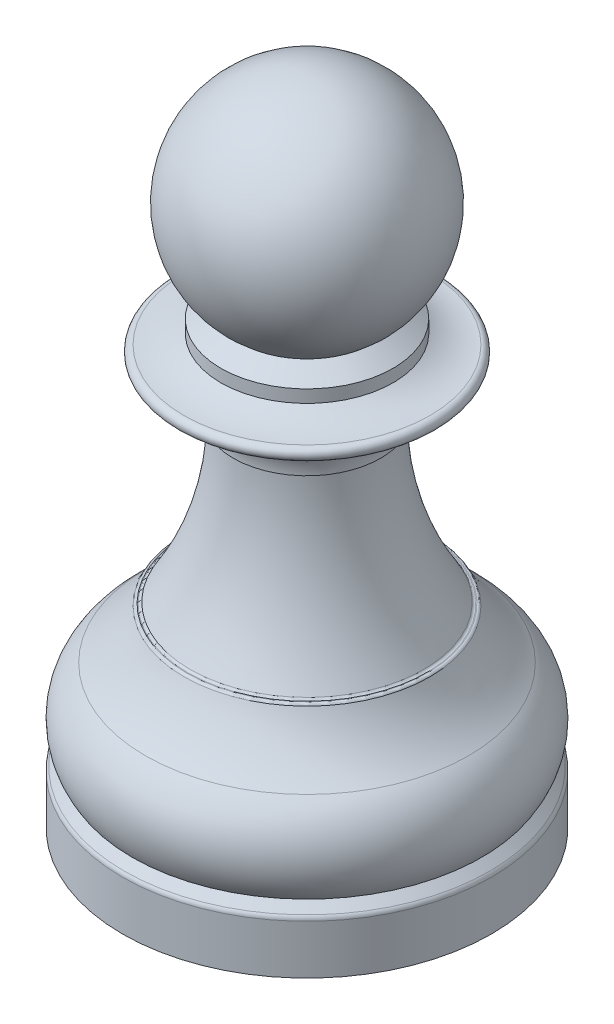
SolidWorks part; units mm, degrees
other "Piece" parameters "D1"=8
ref_plane "Front Plane" through (0, 0, 0) normal (0, 0, 1) x (1, 0, 0)
ref_plane "Top Plane" through (0, 0, 0) normal (0, 1, 0) x (1, 0, 0)
ref_plane "Right Plane" through (0, 0, 0) normal (1, 0, 0) x (0, 0, -1)
sketch "Sketch1" plane through (0, 0, 0) normal (0, 0, 1) x (1, 0, 0)
  line L0 (-15.0008, 0) -> (-15.0008, 4)
  line L1 (-14.2079, 5) -> (-14.8544, 4.3536)
  line L2 (-7, 34.8038) -> (-7, 35.8258)
  line L3 (-5.5, 36.8761) -> (-7, 35.8258)
  line L4 (-10, 33.5) -> (-10, 29) construction
  line L5 (-15.0008, 0) -> (0, 0)
  line L6 (0, 53) -> (0, 0)
  line L7 (0, 0) -> (0, -3.0952) construction
  line L8 (-6, 29) -> (-5.75, 29)
  line L9 (-5.75, 29) -> (-6, 29)
  line L10 (-6, 29) -> (-6, 32.7132) construction
  line L11 (-5.75, 29) -> (-5.75, 35.7914) construction
  line L12 (-9.7727, 15.7558) -> (-9.7123, 15.7558)
  arc A0 (-14.8544, 4.3536) -> (-15.0008, 4) centre (-14.5008, 4) ccw
  arc A1 (-13.1255, 11.6052) -> (-14.2079, 5) centre (-10.0008, 7.7019) ccw
  arc A2 (-13.1255, 11.6052) -> (-10, 15.61) centre (-20, 20.1925) ccw
  arc A3 (-9.7727, 15.7558) -> (-10, 15.61) centre (-9.7727, 15.5058) ccw
  arc A4 (-9.7123, 15.7558) -> (-9.5, 15.8737) centre (-9.7123, 16.0058) ccw
  arc A5 (-9.5, 15.8737) -> (-6.422, 23.2605) centre (-30.5981, 29) ccw
  arc A6 (-6.422, 23.2605) -> (-5.75, 29) centre (-30.5981, 29) ccw
  arc A7 (-6, 29) -> (-6.7812, 31.3748) centre (-10, 29) ccw
  arc A8 (-6.7812, 31.3748) -> (-10, 33) centre (-10, 29) ccw
  arc A9 (-10, 34) -> (-10, 33) centre (-10, 33.5) ccw
  arc A10 (-10, 34) -> (-7, 34.8038) centre (-10, 40) ccw
  arc A11 (0, 53) -> (-5.5, 36.8761) centre (0, 44) ccw
  dimension "D3" = 0.5
  dimension "D8" = 5
  dimension "D12" = 11
  dimension "D15" = 0.25
  dimension "D23" = 10
  dimension "D26" = 0.5
  dimension "D27" = 6
  dimension "D28" = 9
  dimension "D33" = 10
  dimension "D1" = 53
  dimension "D2" = 30.0016
  dimension "D4" = 14.5008
  dimension "D5" = 135
  dimension "D6" = 5
  dimension "D7" = 4
  dimension "D10" = 20
  dimension "D11" = 10.5
  dimension "D13" = 10
  dimension "D14" = 0.25
  dimension "D16" = 5.75
  dimension "D19" = 9.5
  dimension "D24" = 6
  dimension "D29" = 7
  dimension "D30" = 5.5
  dimension "D31" = 55
revolve "Revolve1" add sketch "Sketch1" angle 360 about L7
scale "Scale2" scale about origin uniform scaling yes scale factor 0.766667
sketch "Sketch5" plane through (0, 0, 0) normal (0, -1, 0) x (1, 0, 0)
  point P0 (0, 0)
sketch "Sketch2" plane through (0, 0, 0) normal (0, -1, 0) x (1, 0, 0)
  circle A0 centre (0, 0) radius 10.2
  dimension "D1" = 20.4
extrude "Cut-Extrude1" cut sketch "Sketch2" against normal blind 8
sketch "Sketch6" plane through (0, 8, 0) normal (0, -1, 0) x (1, 0, 0)
  circle A0 centre (0, 0) radius 4.4
  dimension "D1" = 8.8
extrude "Cut-Extrude2" [suppressed] cut sketch "Sketch6" against normal blind 5
sketch "Sketch7" [suppressed] plane through (0, 10, 0) normal (0, -1, 0) x (1, 0, 0)
  circle A0 centre (0, 0) radius 2.2
  dimension "D1" = 4.4
extrude "Cut-Extrude3" [suppressed] cut sketch "Sketch7" against normal blind 13
sketch "Sketch9" plane through (0, 0, 0) normal (0, 0, 1) x (1, 0, 0)
  line L0 (-10.75, 1) -> (0, 1)
  line L1 (-10.75, 1) -> (-10.75, 0)
  line L2 (-10.75, 0) -> (0, 0)
  line L3 (0, 0) -> (0, -1) construction
  line L4 (0, 0) -> (0, 1)
  point P0 (0, 0.75)
  point P4 (-10.2, 0)
  dimension "D1" = 10.2
  dimension "D2" = 1
  dimension "D3" = 0.55
  dimension "D4" = 21.5
revolve "Cut-Revolve1" [suppressed] cut sketch "Sketch9" angle 360 about L3
sketch "Sketch10" plane through (0, 0, 0) normal (0, 0, 1) x (1, 0, 0)
  line L0 (0, 0) -> (-10.55, 0)
  line L1 (0, 0) -> (0, 1)
  line L2 (0, 1) -> (-10.55, 1)
  line L3 (-10.55, 0) -> (-10.55, 1)
  line L4 (0, 0) -> (0, -1.6825) construction
  line L5 (-10.2, 1) -> (-10.2, 0.5)
  line L6 (-10.2, 0.5) -> (0, 0.5)
  dimension "D1" = 21.1
  dimension "D2" = 1
  dimension "D3" = 0.5
  dimension "D4" = 20.4
revolve "Base (White Pawn)" [suppressed] add sketch "Sketch10" angle 360 about L4
sketch "Sketch11" [suppressed] plane through (0, 0, 0) normal (0, 0, 1) x (1, 0, 0)
  line L0 (10.2, 0.5) -> (-10.2, 0.5) construction
  line L1 (-7.5, 2.5) -> (7.5, 2.5)
  line L2 (-7.5, 2.5) -> (-7.5, 0.5)
  line L3 (-7.5, 0.5) -> (7.5, 0.5)
  line L4 (7.5, 2.5) -> (7.5, 0.5)
  line L5 (-7.5, 2.5) -> (7.5, 0.5) construction
  line L6 (-7.5, 0.5) -> (7.5, 2.5) construction
  line L8 (-7.5, 4.5) -> (7.5, 4.5)
  line L9 (-7.5, 4.5) -> (-7.5, 2.5)
  line L10 (-7.5, 2.5) -> (7.5, 2.5)
  line L11 (7.5, 4.5) -> (7.5, 2.5)
  line L12 (-7.5, 4.5) -> (7.5, 2.5) construction
  line L13 (-7.5, 2.5) -> (7.5, 4.5) construction
  line L15 (0, 4.5) -> (0, 0.5) construction
  line L16 (-10.2, 7) -> (10.2, 7) construction
  point P0 (0, 1.5)
  point P7 (0, 3.5)
  point P12 (0, 7)
  point P14 (-10.2, 0.5)
  dimension "D1" = 2
  dimension "D2" = 2
  dimension "D3" = 15
  dimension "D4" = 20.4
  dimension "D5" = 6.5
equation "\"D1@Cut-Extrude1\"=7mm+1mm"
equation "\"D1@Sketch2\"=20.4mm"
equation "\"PawnHeight\"= 1mm"
equation "\"MagDiam\"= 12mm"
equation "\"MagThickness\"= 3mm"
equation "\"KnightHeight\"= 2.5mm"
equation "\"RookHeight\"= 4mm"
equation "\"BishopHeight\"= 5.5mm"
equation "\"QueenHeight\"= 6.5mm"
equation "\"KingHeight\"= 8mm"
equation "\"WeightOuterDiam\"= 18mm"
equation "\"WeightInnerDiam\"= \"MagDiam\" + 0.3mm"
equation "\"WeightHeight\"= 9mm"
equation "\"BaseOuterDiam\"= 20mm"
equation "\"BaseInnerDiam\"= 12.7mm"
equation "\"FeltThickness\"= 1mm"
equation "\"ThreadedDepth\"= 10mm"
equation "\"TapdrillDiam\"= 4.4mm"
equation "\"SocketDepth\"= 5mm"
equation "\"SocketDiam\"= 8.5mm"
equation "\"D1@Sketch6\"=\"SocketDiam\"+0.3"
equation "\"D1@Cut-Extrude2\"=\"SocketDepth\""
equation "\"D1@Sketch7\"=\"TapdrillDiam\""
equation "\"D1@Cut-Extrude3\"=\"ThreadedDepth\"+3mm"
